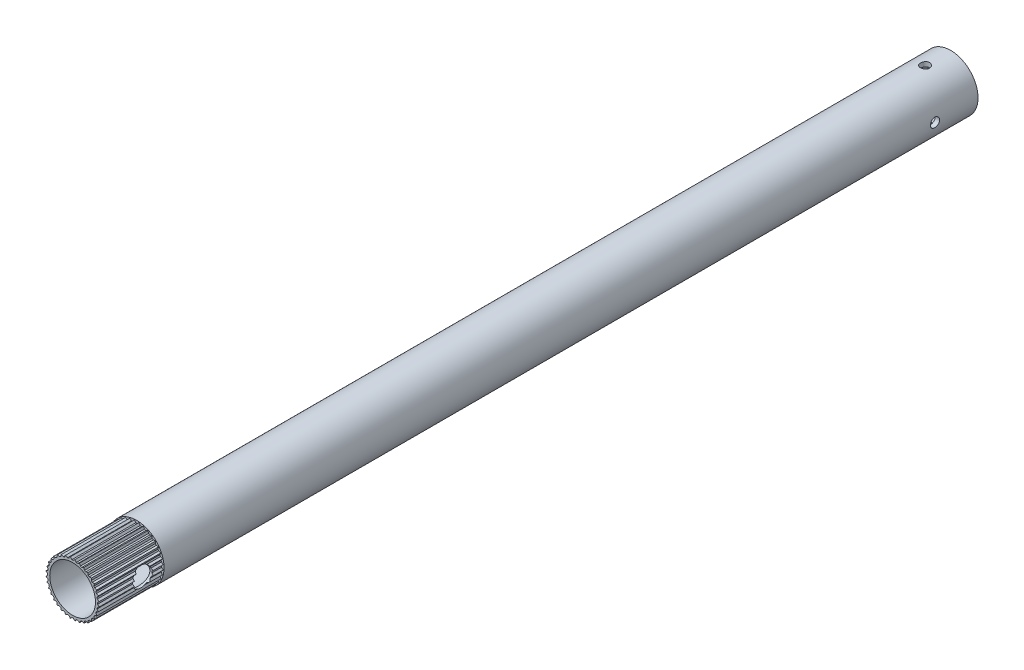
SolidWorks part; units mm, degrees
material "AISI 4130 Steel, normalized at 870C"
ref_plane "X-Y Datum" through (0, 0, 0) normal (0, 0, 1) x (1, 0, 0)
ref_plane "X-Z Datum" through (0, 0, 0) normal (0, 1, 0) x (1, 0, 0)
ref_plane "Y-Z Datum" through (0, 0, 0) normal (1, 0, 0) x (0, 0, -1)
sketch "Sketch1" plane through (0, 0, 0) normal (0, 1, 0) x (1, 0, 0)
  line L0 (9.5377, -364.395) -> (9.5377, -22.1596)
  line L1 (9.5377, -22.1596) -> (7.9375, -22.1596)
  line L2 (7.9375, -22.1596) -> (7.9375, -364.395)
  line L3 (7.9375, -364.395) -> (9.5377, -364.395)
  line L4 (0, -10.4775) -> (0, 10.4775) construction
  line L7 (0, -429.9496) -> (0, 0.9948) construction
revolve "Revolve1" [suppressed] add sketch "Sketch1" angle 360 about L7
sketch "Sketch2" plane through (0, 0, 0) normal (0, 1, 0) x (1, 0, 0)
  circle A0 centre (0, -33.1635) radius 1.5875 construction
  circle A4 centre (0, -33.1635) radius 1.5875
  circle A5 centre (0, -371.1514) radius 3.3782
  circle A6 centre (0, -371.1514) radius 3.3782 construction
extrude "Cut-Extrude2" [suppressed] cut sketch "Sketch2" against normal through all both and the other way through all
sketch "Sketch3" plane through (0, 0, 0) normal (1, 0, 0) x (0, 0, -1)
  circle A1 centre (-39.196, 0) radius 1.5875
  circle A2 centre (-39.196, 0) radius 1.5875 construction
extrude "Cut-Extrude3" [suppressed] cut sketch "Sketch3" against normal through all both and the other way through all
sketch "Sketch5" plane through (0, 0, 0) normal (0, 1, 0) x (1, 0, 0)
  line L0 (7.9375, -329.0759) -> (7.9375, -24.2759)
  line L1 (7.9375, -24.2759) -> (9.525, -24.2759)
  line L2 (9.525, -24.2759) -> (9.525, -329.0759)
  line L3 (9.525, -329.0759) -> (7.9375, -329.0759)
  line L4 (0, 0) -> (0, -348.3259) construction
  line L10 (0, 2.0157) -> (0, -439.4327) construction
  dimension "D1" = 304.8
  dimension "D2" = 1.5875
revolve "Revolve2" add sketch "Sketch5" angle 360 about L10
sketch "Sketch6" plane through (0, 0, 0) normal (0, 1, 0) x (1, 0, 0)
  circle A0 centre (0, -33.1635) radius 1.5875 construction
  circle A1 centre (0, -33.1635) radius 1.5875
sketch "Sketch7" plane through (0, 0, 0) normal (1, 0, 0) x (0, 0, -1)
  circle A0 centre (-313.5823, 0) radius 3.3782 construction
  circle A2 centre (-39.196, 0) radius 1.5875
  circle A3 centre (-313.5823, 0) radius 3.3782
  circle A4 centre (-39.196, 0) radius 1.5875 construction
extrude "Cut-Extrude5" cut sketch "Sketch7" against normal through all both and the other way through all
extrude "Cut-Extrude6" cut sketch "Sketch6" against normal through all both and the other way through all
sketch "Sketch8" plane through (0, 0, 0) normal (0, 0, 1) x (1, 0, 0)
  line L0 (9.2357, -0.808) -> (8.6817, -0.254)
  line L1 (8.6817, -0.254) -> (8.6817, 0.254)
  line L2 (8.6817, 0.254) -> (9.2357, 0.808)
  line L3 (8.6817, 0) -> (0, 0) construction
  line L4 (8.9551, -2.3995) -> (8.5057, -1.7577)
  line L5 (8.5057, -1.7577) -> (8.5939, -1.2574)
  line L6 (8.5939, -1.2574) -> (9.2357, -0.808)
  line L7 (8.4024, -3.9181) -> (8.0713, -3.208)
  line L8 (8.0713, -3.208) -> (8.245, -2.7306)
  line L9 (8.245, -2.7306) -> (8.9551, -2.3995)
  line L10 (7.5944, -5.3176) -> (7.3916, -4.5608)
  line L11 (7.3916, -4.5608) -> (7.6456, -4.1209)
  line L12 (7.6456, -4.1209) -> (8.4024, -3.9181)
  line L13 (6.5556, -6.5556) -> (6.4873, -5.7751)
  line L14 (6.4873, -5.7751) -> (6.8138, -5.3859)
  line L15 (6.8138, -5.3859) -> (7.5944, -5.3176)
  line L16 (5.3176, -7.5944) -> (5.3859, -6.8138)
  line L17 (5.3859, -6.8138) -> (5.7751, -6.4873)
  line L18 (5.7751, -6.4873) -> (6.5556, -6.5556)
  line L19 (3.9181, -8.4024) -> (4.1209, -7.6456)
  line L20 (4.1209, -7.6456) -> (4.5608, -7.3916)
  line L21 (4.5608, -7.3916) -> (5.3176, -7.5944)
  line L22 (2.3995, -8.9551) -> (2.7306, -8.245)
  line L23 (2.7306, -8.245) -> (3.208, -8.0713)
  line L24 (3.208, -8.0713) -> (3.9181, -8.4024)
  line L25 (0.808, -9.2357) -> (1.2574, -8.5939)
  line L26 (1.2574, -8.5939) -> (1.7577, -8.5057)
  line L27 (1.7577, -8.5057) -> (2.3995, -8.9551)
  line L28 (-0.808, -9.2357) -> (-0.254, -8.6817)
  line L29 (-0.254, -8.6817) -> (0.254, -8.6817)
  line L30 (0.254, -8.6817) -> (0.808, -9.2357)
  line L31 (-2.3995, -8.9551) -> (-1.7577, -8.5057)
  line L32 (-1.7577, -8.5057) -> (-1.2574, -8.5939)
  line L33 (-1.2574, -8.5939) -> (-0.808, -9.2357)
  line L34 (-3.9181, -8.4024) -> (-3.208, -8.0713)
  line L35 (-3.208, -8.0713) -> (-2.7306, -8.245)
  line L36 (-2.7306, -8.245) -> (-2.3995, -8.9551)
  line L37 (-5.3176, -7.5944) -> (-4.5608, -7.3916)
  line L38 (-4.5608, -7.3916) -> (-4.1209, -7.6456)
  line L39 (-4.1209, -7.6456) -> (-3.9181, -8.4024)
  line L40 (-6.5556, -6.5556) -> (-5.7751, -6.4873)
  line L41 (-5.7751, -6.4873) -> (-5.3859, -6.8138)
  line L42 (-5.3859, -6.8138) -> (-5.3176, -7.5944)
  line L43 (-7.5944, -5.3176) -> (-6.8138, -5.3859)
  line L44 (-6.8138, -5.3859) -> (-6.4873, -5.7751)
  line L45 (-6.4873, -5.7751) -> (-6.5556, -6.5556)
  line L46 (-8.4024, -3.9181) -> (-7.6456, -4.1209)
  line L47 (-7.6456, -4.1209) -> (-7.3916, -4.5608)
  line L48 (-7.3916, -4.5608) -> (-7.5944, -5.3176)
  line L49 (-8.9551, -2.3995) -> (-8.245, -2.7306)
  line L50 (-8.245, -2.7306) -> (-8.0713, -3.208)
  line L51 (-8.0713, -3.208) -> (-8.4024, -3.9181)
  line L52 (-9.2357, -0.808) -> (-8.5939, -1.2574)
  line L53 (-8.5939, -1.2574) -> (-8.5057, -1.7577)
  line L54 (-8.5057, -1.7577) -> (-8.9551, -2.3995)
  line L55 (-9.2357, 0.808) -> (-8.6817, 0.254)
  line L56 (-8.6817, 0.254) -> (-8.6817, -0.254)
  line L57 (-8.6817, -0.254) -> (-9.2357, -0.808)
  line L58 (-8.9551, 2.3995) -> (-8.5057, 1.7577)
  line L59 (-8.5057, 1.7577) -> (-8.5939, 1.2574)
  line L60 (-8.5939, 1.2574) -> (-9.2357, 0.808)
  line L61 (-8.4024, 3.9181) -> (-8.0713, 3.208)
  line L62 (-8.0713, 3.208) -> (-8.245, 2.7306)
  line L63 (-8.245, 2.7306) -> (-8.9551, 2.3995)
  line L64 (-7.5944, 5.3176) -> (-7.3916, 4.5608)
  line L65 (-7.3916, 4.5608) -> (-7.6456, 4.1209)
  line L66 (-7.6456, 4.1209) -> (-8.4024, 3.9181)
  line L67 (-6.5556, 6.5556) -> (-6.4873, 5.7751)
  line L68 (-6.4873, 5.7751) -> (-6.8138, 5.3859)
  line L69 (-6.8138, 5.3859) -> (-7.5944, 5.3176)
  line L70 (-5.3176, 7.5944) -> (-5.3859, 6.8138)
  line L71 (-5.3859, 6.8138) -> (-5.7751, 6.4873)
  line L72 (-5.7751, 6.4873) -> (-6.5556, 6.5556)
  line L73 (-3.9181, 8.4024) -> (-4.1209, 7.6456)
  line L74 (-4.1209, 7.6456) -> (-4.5608, 7.3916)
  line L75 (-4.5608, 7.3916) -> (-5.3176, 7.5944)
  line L76 (-2.3995, 8.9551) -> (-2.7306, 8.245)
  line L77 (-2.7306, 8.245) -> (-3.208, 8.0713)
  line L78 (-3.208, 8.0713) -> (-3.9181, 8.4024)
  line L79 (-0.808, 9.2357) -> (-1.2574, 8.5939)
  line L80 (-1.2574, 8.5939) -> (-1.7577, 8.5057)
  line L81 (-1.7577, 8.5057) -> (-2.3995, 8.9551)
  line L82 (0.808, 9.2357) -> (0.254, 8.6817)
  line L83 (0.254, 8.6817) -> (-0.254, 8.6817)
  line L84 (-0.254, 8.6817) -> (-0.808, 9.2357)
  line L85 (2.3995, 8.9551) -> (1.7577, 8.5057)
  line L86 (1.7577, 8.5057) -> (1.2574, 8.5939)
  line L87 (1.2574, 8.5939) -> (0.808, 9.2357)
  line L88 (3.9181, 8.4024) -> (3.208, 8.0713)
  line L89 (3.208, 8.0713) -> (2.7306, 8.245)
  line L90 (2.7306, 8.245) -> (2.3995, 8.9551)
  line L91 (5.3176, 7.5944) -> (4.5608, 7.3916)
  line L92 (4.5608, 7.3916) -> (4.1209, 7.6456)
  line L93 (4.1209, 7.6456) -> (3.9181, 8.4024)
  line L94 (6.5556, 6.5556) -> (5.7751, 6.4873)
  line L95 (5.7751, 6.4873) -> (5.3859, 6.8138)
  line L96 (5.3859, 6.8138) -> (5.3176, 7.5944)
  line L97 (7.5944, 5.3176) -> (6.8138, 5.3859)
  line L98 (6.8138, 5.3859) -> (6.4873, 5.7751)
  line L99 (6.4873, 5.7751) -> (6.5556, 6.5556)
  line L100 (8.4024, 3.9181) -> (7.6456, 4.1209)
  line L101 (7.6456, 4.1209) -> (7.3916, 4.5608)
  line L102 (7.3916, 4.5608) -> (7.5944, 5.3176)
  line L103 (8.9551, 2.3995) -> (8.245, 2.7306)
  line L104 (8.245, 2.7306) -> (8.0713, 3.208)
  line L105 (8.0713, 3.208) -> (8.4024, 3.9181)
  line L106 (9.2357, 0.808) -> (8.5939, 1.2574)
  line L107 (8.5939, 1.2574) -> (8.5057, 1.7577)
  line L108 (8.5057, 1.7577) -> (8.9551, 2.3995)
  circle A0 centre (0, 0) radius 12.7
  circle A1 centre (0, 0) radius 9.271 construction
  circle A2 centre (0, 0) radius 8.6854 construction
  point P153 (0, 0)
  dimension "D1" = 25.4
  dimension "D4" = 18.542
  dimension "D6" = 17.3708
  dimension "D2" = 0.508
  dimension "D3" = 135
  dimension "D5" = 36
extrude "Cut-Extrude7" cut sketch "Sketch8" against normal blind 22.225 from surface at 329.0759 starting at face at (-9.525, 0, 329.0759)
